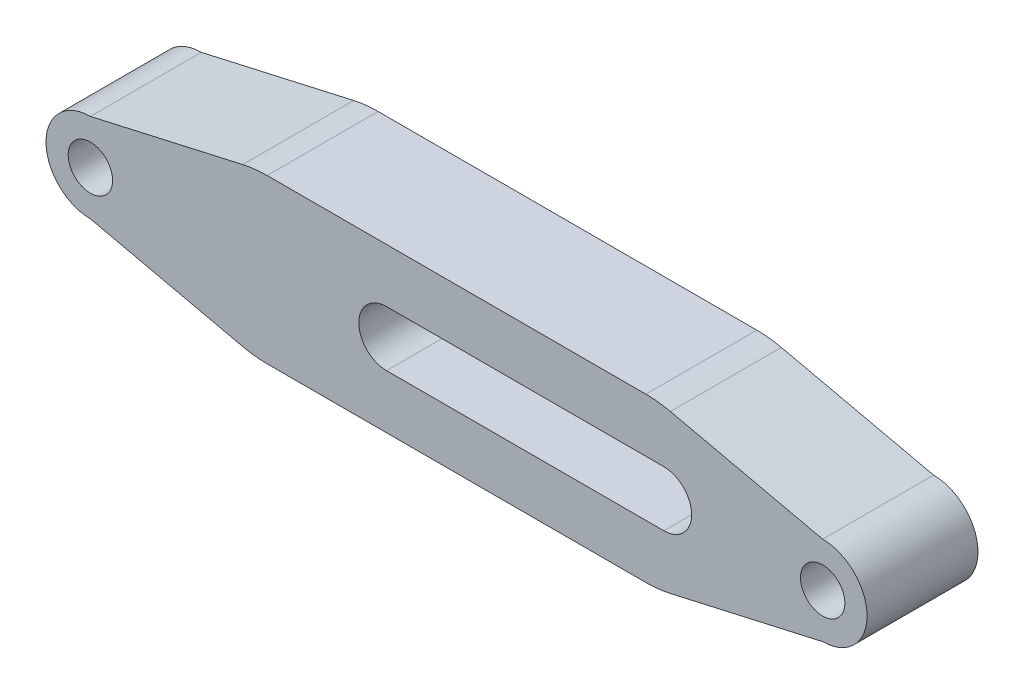
SolidWorks part; units mm, degrees
ref_plane "Alzado" through (0, 0, 0) normal (0, 0, 1) x (1, 0, 0)
ref_plane "Planta" through (0, 0, 0) normal (0, 1, 0) x (1, 0, 0)
ref_plane "Vista lateral" through (0, 0, 0) normal (1, 0, 0) x (0, 0, -1)
sketch "Croquis1" plane through (0, 0, 0) normal (0, 0, 1) x (1, 0, 0)
  line L0 (0, 0) -> (66, 0) construction
  line L1 (14.815, 7.35) -> (51.185, 7.35)
  line L2 (0, 4) -> (14.815, 7.35)
  line L3 (51.185, 7.35) -> (66, 4)
  line L4 (51.185, -7.35) -> (66, -4)
  line L5 (14.815, -7.35) -> (51.185, -7.35)
  line L6 (0, -4) -> (14.815, -7.35)
  circle A0 centre (0, 0) radius 2
  arc A1 (0, 4) -> (0, -4) centre (0, 0) ccw
  arc A2 (66, -4) -> (66, 4) centre (66, 0) ccw
  circle A3 centre (66, 0) radius 2
  point P10 (33, 7.35)
  point P11 (33, 0)
  dimension "D1" = 4
  dimension "D2" = 8
  dimension "D3" = 66
  dimension "D4" = 7.35
  dimension "D5" = 36.37
extrude "Saliente-Extruir1" add sketch "Croquis1" along normal blind 10
fillet "Redondeo2" radius 10 4 edges at (14.815, -7.35, 5) (14.815, 7.35, 5) (51.185, 7.35, 5) (51.185, -7.35, 5)
sketch "Croquis2" plane through (0, 0, 0) normal (0, 0, 1) x (1, 0, 0)
  line L0 (70, 0) -> (51.69, 0) construction
  line L1 (51.69, 2.5) -> (26.69, 2.5)
  line L2 (70, 0) -> (-4, 0) construction
  line L3 (51.69, -2.5) -> (26.69, -2.5)
  arc A0 (66, -4) -> (66, 4) centre (66, 0) ccw construction
  arc A1 (51.69, -2.5) -> (51.69, 2.5) centre (51.69, 0) ccw
  arc A2 (0, 4) -> (0, -4) centre (0, 0) ccw construction
  arc A3 (26.69, -2.5) -> (26.69, 2.5) centre (26.69, 0) cw
  dimension "D2" = 25
  dimension "D3" = 5
  dimension "D1" = 18.31
extrude "Cortar-Extruir1" cut sketch "Croquis2" along normal up to surface (10 mm away) up to face at (2, 0, 10)
